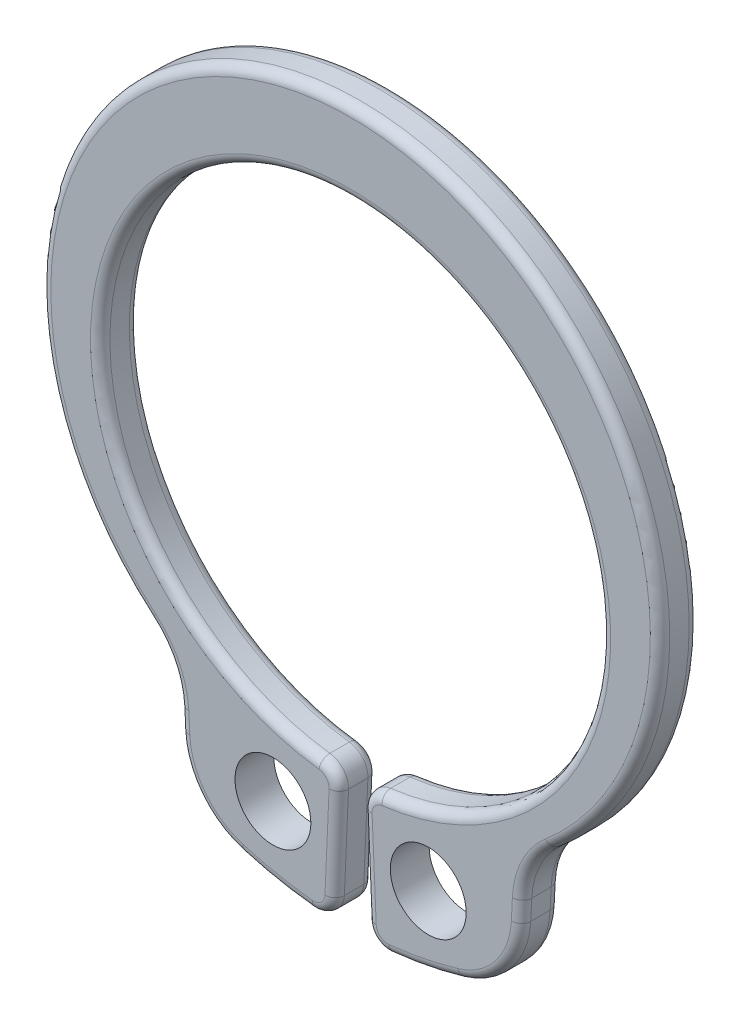
SolidWorks part; units mm, degrees
material "201 Annealed Stainless Steel (SS)"
ref_plane "Front" through (0, 0, 0) normal (0, 0, 1) x (1, 0, 0)
ref_plane "Top" through (0, 0, 0) normal (0, 1, 0) x (1, 0, 0)
ref_plane "Right" through (0, 0, 0) normal (1, 0, 0) x (0, 0, -1)
sketch "Sketch1" plane through (0, 0, 0) normal (0, 0, 1) x (1, 0, 0)
  line L0 (0, 0) -> (-5.5859, -3.225) construction
  line L1 (0, 9.95) -> (0, -9.95) construction
  line L2 (-4.3233, -8.9722) -> (-4.4664, -6.025) construction
  line L3 (0, 0) -> (5.5859, -3.225) construction
  line L4 (-4.4664, -6.025) -> (-5.0917, -6.8686) construction
  line L5 (-4.4664, -6.025) -> (0, 0) construction
  line L6 (0, 6.45) -> (0, 8.55) construction
  line L7 (0, 8.55) -> (0, 7.5) construction
  line L8 (0, -6.45) -> (0, -9.95) construction
  line L9 (-2.4286, -9.6588) -> (0, 0) construction
  line L10 (0, 0) -> (-0.4344, -9.95) construction
  line L11 (-4.3233, -8.9722) -> (0, 0) construction
  line L12 (-4.4232, -6.9148) -> (-5.1752, -5.4855) construction
  line L13 (-4.7992, -6.2001) -> (-4.4664, -6.025) construction
  line L14 (-1.5728, -6.2553) -> (-2.4286, -9.6588) construction
  line L15 (-2.0007, -7.9571) -> (-1.1764, -8.1643) construction
  arc A0 (0, 8.55) -> (-4.4664, -6.025) centre (0, 0.5781) ccw construction
  circle A2 centre (0, 0) radius 8.55 construction
  arc A3 (-4.3233, -8.9722) -> (-0.4344, -9.95) centre (0, 0) ccw construction
  circle A4 centre (0, 0) radius 6.45 construction
  circle A6 centre (-2.0007, -7.9571) radius 0.85 construction
  arc A7 (-5.1752, -5.4855) -> (-4.4232, -6.9148) centre (-6.5887, -7.1417) cw construction
  point P5 (-5.5859, -3.225)
  point P11 (5.5859, -3.225)
  point P24 (-3.7115, -7.7024)
  point P35 (0, 8.55)
  point P36 (0, 6.45)
  point P37 (0, -6.45)
  point P38 (0, -9.95)
  dimension "Ring ID" = 12.9
  dimension "Hole Diameter" = 1.7
  dimension "D10" = 2.1774
  dimension "Max Sec." = 2.1
  dimension "Lug Height" = 3.5
  dimension "D6" = 2.5
  dimension "D5" = 2.9506
  dimension "D8" = 1.615
  dimension "D3" = 120
  dimension "D7" = 60
  dimension "D2" = 4.0375
  dimension "D4" = 1.615
sketch "Sketch5" plane through (0, 0, 0) normal (0, 1, 0) x (1, 0, 0)
  line L0 (-8.55, 0.5) -> (-8.55, -0.5) construction
  line L2 (0, 0.5) -> (0, -0.5) construction
  line L4 (-8.55, 0) -> (8.55, 0) construction
  point P3 (-8.55, 0)
  point P6 (0, 0)
  dimension "Ring Thickness" = 1
sketch "Sketch2" plane through (0, 0, 0) normal (0, 0, 1) x (1, 0, 0)
  line L0 (-4.3233, -8.9722) -> (-4.4664, -6.025) construction
  line L1 (-4.3233, -8.9722) -> (-4.4664, -6.025)
  line L2 (0, 8.55) -> (0, 6.45)
  line L3 (-0.4344, -9.95) -> (-0.2813, -6.4439)
  line L4 (0, 0) -> (-0.4344, -9.95) construction
  arc A0 (0, 8.55) -> (-4.4664, -6.025) centre (0, 0.5781) ccw construction
  arc A1 (-4.3233, -8.9722) -> (-0.4344, -9.95) centre (0, 0) ccw construction
  circle A2 centre (-2.0007, -7.9571) radius 0.85 construction
  circle A3 centre (-2.0007, -7.9571) radius 0.9775
  arc A4 (0, 8.55) -> (-4.4664, -6.025) centre (0, 0.5781) ccw
  arc A5 (-4.3233, -8.9722) -> (-0.4344, -9.95) centre (0, 0) ccw
  circle A6 centre (-2.0007, -7.9571) radius 0.85 construction
  circle A7 centre (0, 0) radius 6.45 construction
  arc A8 (0, 6.45) -> (-0.2813, -6.4439) centre (0, 0) ccw
  dimension "D1" = 1.955
extrude "Boss-Extrude1" add sketch "Sketch2" along normal mid plane 1
fillet "Fillet1" radius 2.1774 2 edges at (-4.4664, -6.025, 0) (-4.3233, -8.9722, 0)
fillet "Fillet2" radius 0.5443 2 edges at (-0.4344, -9.95, 0) (-0.2813, -6.4439, 0)
mirror "Mirror1" about plane through (0, 8.55, 0.5) normal (-1, 0, 0) of bodies 109
fillet "Fillet3" radius 0.25 32 edges at (-0.4326, -6.5909, -0.5) (-0.3571, -8.1785, -0.5) (-0.5978, -9.7785, -0.5) (-1.9315, -9.7704, -0.5) (-3.9299, -8.8037, -0.5) (-4.4045, -7.2992, -0.5) (-4.6375, -6.1795, -0.5) (0, 8.55, -0.5) (4.6375, -6.1795, 0.5) (4.6375, -6.1795, -0.5) (4.4045, -7.2992, -0.5) (4.4045, -7.2992, 0.5) (3.9299, -8.8037, 0.5) (3.9299, -8.8037, -0.5) (1.9315, -9.7704, -0.5) (1.9315, -9.7704, 0.5) (0.5978, -9.7785, 0.5) (0.5978, -9.7785, -0.5) (0.3571, -8.1785, 0.5) (0.3571, -8.1785, -0.5) (0.4326, -6.5909, 0.5) (0.4326, -6.5909, -0.5) (-0.4326, -6.5909, 0.5) (-0.3571, -8.1785, 0.5) (-0.5978, -9.7785, 0.5) (-1.9315, -9.7704, 0.5) (-3.9299, -8.8037, 0.5) (-4.4045, -7.2992, 0.5) (-4.6375, -6.1795, 0.5) (0, 8.55, 0.5) (0, 6.45, -0.5) (0, 6.45, 0.5)
sketch "Sketch3" plane through (0, 0, 0.5) normal (0, 0, 1) x (1, 0, 0)
  line L0 (4.4679, -4.6519) -> (5.178, -5.4831) construction
  line L1 (5.178, -5.4831) -> (6.0092, -4.773) construction
  line L2 (0, 8.55) -> (0, 6.45) construction
  circle A0 centre (0, 0) radius 6.45 construction
  arc A1 (-5.178, -5.4831) -> (5.178, -5.4831) centre (0, 0.5781) ccw construction
equation "\"Thickness@Boss-Extrude1\"=\"Ring Thickness@Sketch5\""
equation "\"D2@Sketch1\"=\"Hole Diameter@Sketch1\"*2.375"
equation "\"D4@Sketch1\"=\"D2@Sketch1\"/2.5"
equation "\"D8@Sketch1\"=\"D4@Sketch1\""
equation "\"D1@Sketch2\"=\"Hole Diameter@Sketch1\"*1.15"
equation "\"D1@Fillet2\"=\"D10@Sketch1\" / 4"
equation "\"D1@Fillet3\"=\"Ring Thickness@Sketch5\"/4"
equation "\"D1@Fillet1\"=\"D10@Sketch1\""
